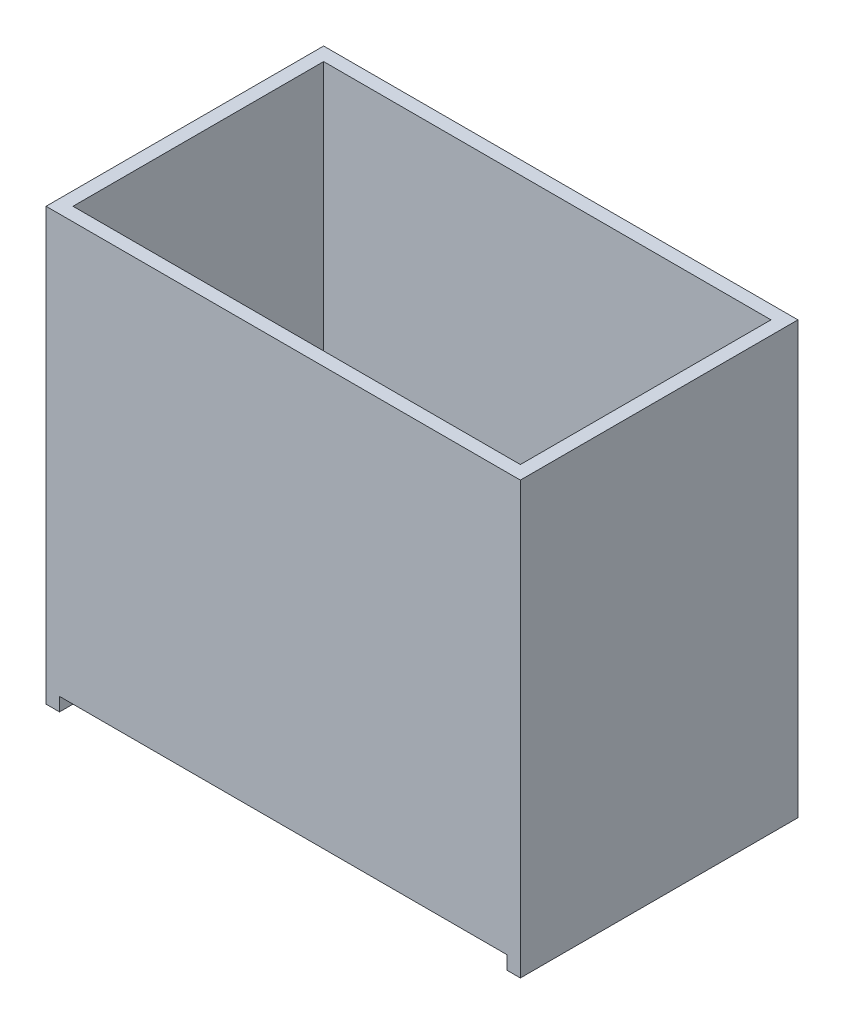
SolidWorks part; units mm, degrees
material "Acrylic (Medium-high impact)"
ref_plane "Front Plane" through (0, 0, 0) normal (0, 0, 1) x (1, 0, 0)
ref_plane "Top Plane" through (0, 0, 0) normal (0, 1, 0) x (1, 0, 0)
ref_plane "Right Plane" through (0, 0, 0) normal (1, 0, 0) x (0, 0, -1)
sketch "Sketch1" plane through (0, 0, 0) normal (0, 1, 0) x (1, 0, 0)
  line L1 (0, 0) -> (176, 0)
  line L2 (0, 0) -> (0, 103)
  line L3 (0, 103) -> (176, 103)
  line L4 (176, 0) -> (176, 103)
  line L5 (5, 5) -> (171, 5)
  line L6 (5, 5) -> (5, 98)
  line L7 (5, 98) -> (171, 98)
  line L8 (171, 5) -> (171, 98)
  dimension "D1" = 5
  dimension "D2" = 5
  dimension "D3" = 5
  dimension "D4" = 5
  dimension "D5" = 176
  dimension "D6" = 103
extrude "Boss-Extrude1" add sketch "Sketch1" along normal blind 160
sketch "Sketch2" plane through (0, 0, 0) normal (0, 0, 1) x (1, 0, 0)
  line L0 (176, 160) -> (176, 0) construction
  line L1 (5, 0) -> (171, 0)
  line L2 (5, 0) -> (5, 5)
  line L3 (5, 5) -> (171, 5)
  line L4 (171, 0) -> (171, 5)
  dimension "D1" = 5
  dimension "D2" = 5
extrude "Cut-Extrude1" cut sketch "Sketch2" against normal up to next
